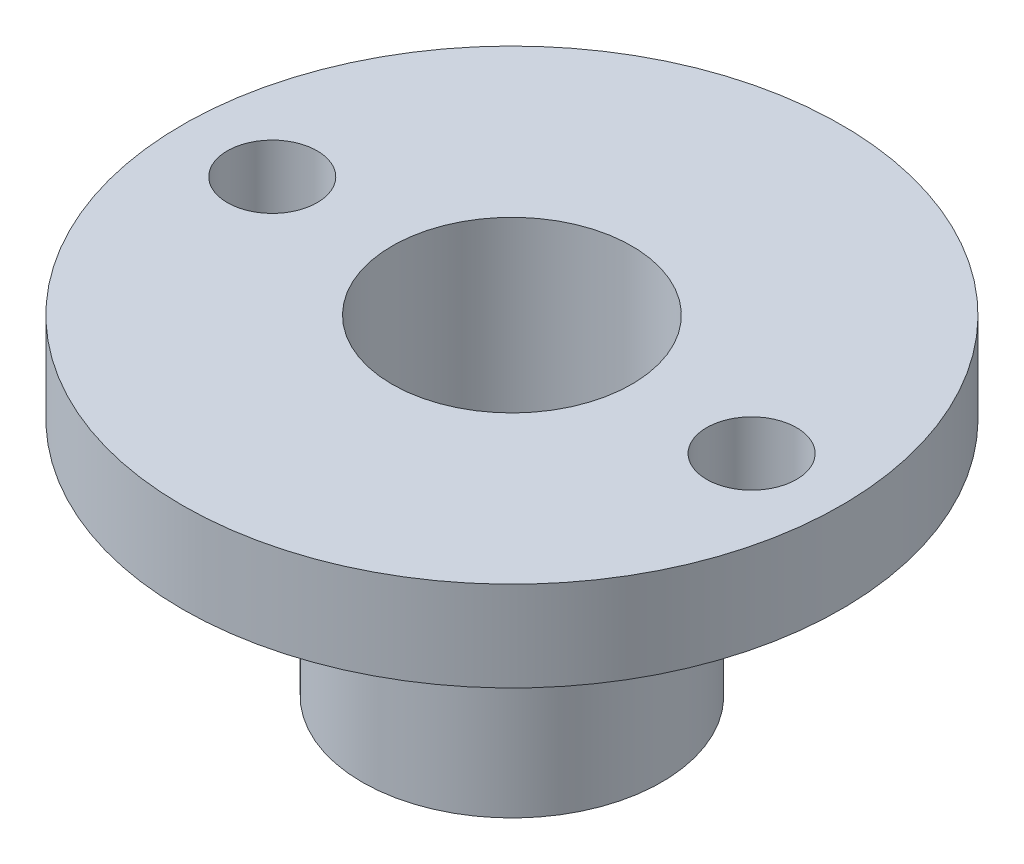
SolidWorks part; units mm, degrees
material "2.0966 (CuAl10Ni5Fe4)"
ref_plane "Přední rovina" through (0, 0, 0) normal (0, 0, 1) x (1, 0, 0)
ref_plane "Horní rovina" through (0, 0, 0) normal (0, 1, 0) x (1, 0, 0)
ref_plane "Pravá rovina" through (0, 0, 0) normal (1, 0, 0) x (0, 0, -1)
sketch "Skica1" plane through (0, 0, 0) normal (0, 1, 0) x (1, 0, 0)
  circle A0 centre (0, 0) radius 4
  circle A1 centre (0, 0) radius 5
  dimension "D1" = 8
  dimension "D2" = 10
extrude "Přidat vysunutím1" add sketch "Skica1" along normal blind 8
sketch "Skica2" plane through (0, 8, 0) normal (0, 1, 0) x (1, 0, 0)
  circle A0 centre (0, 0) radius 4
  circle A1 centre (0, 0) radius 11
  dimension "D1" = 22
extrude "Přidat vysunutím2" add sketch "Skica2" along normal blind 3
sketch "Skica3" plane through (0, 11, 0) normal (0, 1, 0) x (1, 0, 0)
  circle A0 centre (0, 0) radius 8 construction
  circle A1 centre (-8, 0) radius 1.5
  circle A2 centre (8, 0) radius 1.5
  dimension "D1" = 16
  dimension "D2" = 3
extrude "Odebrat vysunutím3" cut sketch "Skica3" against normal up to surface (3 mm away) contours A2 | A1 up to face at (0, 8, 5)
